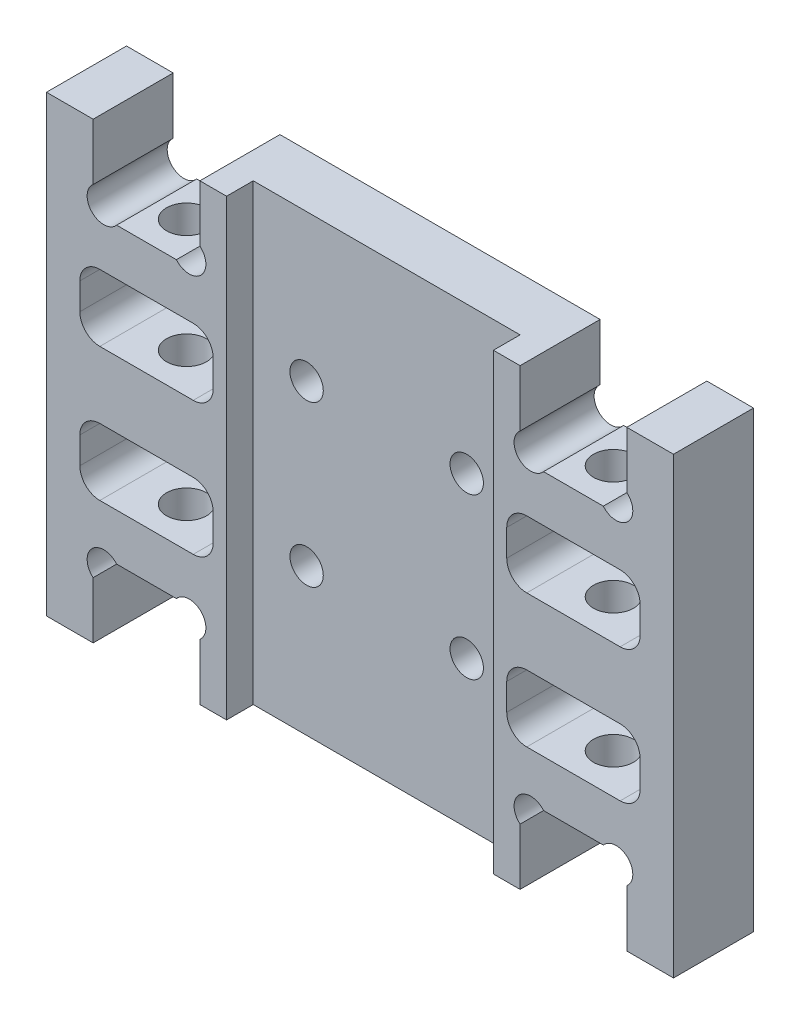
SolidWorks part; units mm, degrees
ref_plane "前视基准面" through (0, 0, 0) normal (0, 0, 1) x (1, 0, 0)
ref_plane "上视基准面" through (0, 0, 0) normal (0, 1, 0) x (1, 0, 0)
ref_plane "右视基准面" through (0, 0, 0) normal (1, 0, 0) x (0, 0, -1)
sketch "草图1" plane through (0, 0, 0) normal (0, 0, 1) x (1, 0, 0)
  line L0 (0, 86.7562) -> (0, -64.6665) construction
  line L1 (-73.9598, 0) -> (104.5329, 0) construction
  line L2 (-25, -17) -> (-25, 17)
  line L3 (-25, 17) -> (-22, 17)
  line L4 (-22, 17) -> (-22, 11)
  line L5 (-22, 11) -> (-12, 11)
  line L6 (-12, 11) -> (-12, 17)
  line L7 (-12, 17) -> (12, 17)
  line L8 (-12, -17) -> (12, -17)
  line L9 (-12, -11) -> (-12, -17)
  line L10 (-22, -11) -> (-12, -11)
  line L11 (-22, -17) -> (-22, -11)
  line L12 (-25, -17) -> (-22, -17)
  line L13 (25, -17) -> (22, -17)
  line L14 (22, -17) -> (22, -11)
  line L15 (22, -11) -> (12, -11)
  line L16 (12, -11) -> (12, -17)
  line L17 (12, 11) -> (12, 17)
  line L18 (22, 11) -> (12, 11)
  line L19 (22, 17) -> (22, 11)
  line L20 (25, 17) -> (22, 17)
  line L21 (25, -17) -> (25, 17)
  line L22 (-17, 11) -> (-17, -11) construction
  line L23 (-23, 11) -> (-23, -11) construction
  line L24 (-11, 11) -> (-11, -11) construction
  point P18 (-25, 0)
  point P23 (0, -17)
  point P24 (0, 17)
  point P28 (25, 0)
  dimension "D1" = 17
  dimension "D2" = 6
  dimension "D3" = 10
  dimension "D4" = 3
  dimension "D5" = 17
  dimension "D6" = 6
  dimension "D7" = 6
extrude "凸台-拉伸1" add sketch "草图1" along normal blind 6
sketch "草图2" plane through (0, 0, 6) normal (0, 0, 1) x (1, 0, 0)
  line L0 (-16, 14) -> (-16, -10) construction
  line L3 (-25, 0) -> (25, 0) construction
  line L4 (-25, 17) -> (-25, -17) construction
  line L5 (25, -17) -> (25, 17) construction
  line L6 (-21, -2.5) -> (-11, -7.5) construction
  line L7 (-21, 7.5) -> (-11, 7.5)
  line L8 (-21, 7.5) -> (-21, 2.5)
  line L9 (-21, 2.5) -> (-11, 2.5)
  line L10 (-11, 7.5) -> (-11, 2.5)
  line L11 (-21, 7.5) -> (-11, 2.5) construction
  line L12 (-21, 2.5) -> (-11, 7.5) construction
  line L13 (-21, -7.5) -> (-11, -2.5) construction
  line L14 (-11, -7.5) -> (-11, -2.5)
  line L15 (-21, -2.5) -> (-11, -2.5)
  line L16 (-21, -7.5) -> (-21, -2.5)
  line L17 (-21, -7.5) -> (-11, -7.5)
  line L18 (0, 17) -> (0, -17) construction
  line L19 (12, 17) -> (-12, 17) construction
  line L20 (-12, -17) -> (12, -17) construction
  line L21 (21, -7.5) -> (11, -2.5) construction
  line L22 (21, 2.5) -> (11, 7.5) construction
  line L23 (21, 7.5) -> (11, 2.5) construction
  line L24 (21, -2.5) -> (11, -7.5) construction
  line L25 (16, 14) -> (16, -10) construction
  line L26 (21, -7.5) -> (11, -7.5)
  line L27 (21, -7.5) -> (21, -2.5)
  line L28 (21, -2.5) -> (11, -2.5)
  line L29 (11, -7.5) -> (11, -2.5)
  line L30 (11, 7.5) -> (11, 2.5)
  line L31 (21, 2.5) -> (11, 2.5)
  line L32 (21, 7.5) -> (21, 2.5)
  line L33 (21, 7.5) -> (11, 7.5)
  line L34 (11, 2.5) -> (21, -2.5) construction
  line L35 (-11, -2.5) -> (-21, -2.5) construction
  line L36 (-11, -2.5) -> (-11, 2.5) construction
  line L37 (-11, 2.5) -> (-21, 2.5) construction
  line L38 (-21, -2.5) -> (-21, 2.5) construction
  line L39 (-11, -2.5) -> (-21, 2.5) construction
  line L40 (-11, 2.5) -> (-21, -2.5) construction
  line L41 (11, -2.5) -> (21, 2.5) construction
  line L42 (21, -2.5) -> (21, 2.5) construction
  line L43 (11, 2.5) -> (21, 2.5) construction
  line L44 (11, -2.5) -> (11, 2.5) construction
  line L45 (11, -2.5) -> (21, -2.5) construction
  point P2 (-16, 0)
  point P12 (-16, 5)
  point P17 (-16, 2)
  point P22 (-16, -5)
  point P39 (16, -5)
  point P40 (16, 5)
  point P46 (16, 0)
  dimension "D1" = 10
  dimension "D2" = 5
  dimension "D3" = 12
  dimension "D4" = 5
  dimension "D5" = 16
  dimension "D6" = 5
  dimension "D7" = 10
extrude "切除-拉伸1" cut sketch "草图2" against normal through all
sketch "草图3" plane through (0, -11, 0) normal (0, -1, 0) x (1, 0, 0)
  line L0 (-25, 3) -> (25, 3) construction
  line L1 (-25, 6) -> (-25, 0) construction
  line L2 (25, 6) -> (25, 0) construction
  line L3 (-16, 6) -> (-16, 0) construction
  line L5 (-22, 0) -> (-12, 0) construction
  line L6 (0, 0) -> (0, 6) construction
  line L7 (-12, 6) -> (12, 6) construction
  line L8 (-12, 6) -> (-12, 0) construction
  circle A0 centre (-16, 3) radius 1.5
  circle A1 centre (16, 3) radius 1.5
  dimension "D1" = 3
  dimension "D2" = 4
extrude "切除-拉伸2" cut sketch "草图3" against normal through all
sketch "草图4" plane through (0, 0, 6) normal (0, 0, 1) x (1, 0, 0)
  line L1 (-10, 17) -> (10, 17)
  line L2 (-10, 17) -> (-10, -17)
  line L3 (-10, -17) -> (10, -17)
  line L4 (10, 17) -> (10, -17)
  line L5 (-10, 17) -> (10, -17) construction
  line L6 (-10, -17) -> (10, 17) construction
  line L7 (-12, -17) -> (12, -17) construction
  point P0 (0, 0)
  dimension "D1" = 20
extrude "切除-拉伸3" cut sketch "草图4" against normal blind 2
sketch "草图5" plane through (0, 0, 4) normal (0, 0, 1) x (1, 0, 0)
  line L1 (-6, 6) -> (6, 6) construction
  line L2 (-6, 6) -> (-6, -6) construction
  line L3 (-6, -6) -> (6, -6) construction
  line L4 (6, 6) -> (6, -6) construction
  line L5 (-6, 6) -> (6, -6) construction
  line L6 (-6, -6) -> (6, 6) construction
  circle A0 centre (-6, 6) radius 1.25
  circle A1 centre (6, 6) radius 1.25
  circle A2 centre (-6, -6) radius 1.25
  circle A3 centre (6, -6) radius 1.25
  point P0 (0, 0)
  dimension "D3" = 2.5
  dimension "D1" = 12
  dimension "D2" = 12
extrude "切除-拉伸4" cut sketch "草图5" against normal through all
cosmetic thread "装饰螺纹线1" [suppressed] parameters "D2"=4
cosmetic thread "装饰螺纹线2" [suppressed] parameters "D2"=4
cosmetic thread "装饰螺纹线3" [suppressed] parameters "D2"=4
cosmetic thread "装饰螺纹线4" [suppressed] parameters "D2"=4
sketch "草图6" plane through (0, 0, 6) normal (0, 0, 1) x (1, 0, 0)
  line L0 (0, 22.7228) -> (0, -22.1506) construction
  line L1 (-12, 14) -> (12, 14) construction
  line L2 (-12, 17) -> (-12, 11) construction
  line L3 (12, 11) -> (12, 17) construction
  line L4 (-10, 17) -> (-10, -17) construction
  line L5 (-13, 15.5) -> (-1, 15.5) construction
  line L6 (-13, 15.5) -> (-13, 12.5) construction
  line L7 (-13, 12.5) -> (-1, 12.5) construction
  line L8 (-1, 15.5) -> (-1, 12.5) construction
  line L9 (-13, 15.5) -> (-1, 12.5) construction
  line L10 (-13, 12.5) -> (-1, 15.5) construction
  line L11 (-12, 11) -> (-22, 11) construction
  line L12 (-22, -11) -> (-12, -11) construction
  line L13 (0, 0) -> (25, 0) construction
  line L14 (25, -17) -> (25, 17) construction
  circle A0 centre (-7, 14) radius 1.5
  circle A1 centre (7, 14) radius 1.5
  circle A2 centre (7, -14) radius 1.5
  circle A3 centre (-7, -14) radius 1.5
  point P9 (-7, 14)
  point P14 (0, 14)
  dimension "D5" = 3
  dimension "D1" = 12
  dimension "D2" = 12
  dimension "D3" = 7
  dimension "D4" = 3
  dimension "D6" = 3
  dimension "D7" = 22
extrude "切除-拉伸6" [suppressed] cut sketch "草图6" against normal through all contours A0 | A1 | A3 | A2
cosmetic thread "装饰螺纹线5" [suppressed] parameters "D2"=4
cosmetic thread "装饰螺纹线6" [suppressed] parameters "D2"=4
cosmetic thread "装饰螺纹线7" [suppressed] parameters "D2"=4
cosmetic thread "装饰螺纹线8" [suppressed] parameters "D2"=4
sketch "草图7" plane through (0, 0, 6) normal (0, 0, 1) x (1, 0, 0)
  line L1 (-10, 17) -> (-12, 17) construction
  line L2 (-11.5, 17) -> (11.5, 17)
  line L3 (-11.5, 17) -> (-11.5, 11)
  line L4 (-11.5, 11) -> (11.5, 11)
  line L5 (11.5, 17) -> (11.5, 11)
  line L6 (22, 11) -> (12, 11) construction
  line L7 (-10, 17) -> (-10, -17) construction
  line L8 (10, -17) -> (10, 17) construction
  line L9 (-29.3966, 0) -> (33.4524, 0) construction
  line L10 (11.5, -17) -> (11.5, -11)
  line L11 (-11.5, -11) -> (11.5, -11)
  line L12 (-11.5, -17) -> (-11.5, -11)
  line L13 (-11.5, -17) -> (11.5, -17)
  dimension "D1" = 1.5
  dimension "D2" = 1.5
extrude "切除-拉伸8" [suppressed] cut sketch "草图7" against normal up to surface (2 mm away)
fillet "圆角1" [suppressed] radius 1.5
sketch "草图8" plane through (0, 0, 6) normal (0, 0, 1) x (1, 0, 0)
  circle A0 centre (-22, 11) radius 1
  circle A1 centre (-12, 11) radius 1
  circle A2 centre (12, 11) radius 1
  circle A3 centre (22, 11) radius 1
  circle A4 centre (-22, -11) radius 1
  circle A5 centre (-12, -11) radius 1
  circle A6 centre (12, -11) radius 1
  circle A7 centre (22, -11) radius 1
  dimension "D1" = 2
extrude "切除-拉伸9" [suppressed] cut sketch "草图8" against normal through all
fillet "圆角2" radius 1.5 16 edges at (21, -7.5, 3) (11, -7.5, 3) (21, 2.5, 3) (21, 7.5, 3) (11, 2.5, 3) (11, 7.5, 3) (-11, -7.5, 3) (-21, -7.5, 3) (-21, -2.5, 3) (-11, -2.5, 3) (-21, 2.5, 3) (-11, 2.5, 3) (-11, 7.5, 3) (-21, 7.5, 3) (11, -2.5, 3) (21, -2.5, 3)
sketch "草图9" plane through (0, 0, 6) normal (0, 0, 1) x (1, 0, 0)
  line L1 (-25, 17) -> (-23.5, 17)
  line L2 (-25, 17) -> (-25, -18)
  line L3 (-25, -18) -> (-23.5, -18)
  line L4 (-23.5, 17) -> (-23.5, -18)
  line L6 (25, 17) -> (23.5, 17)
  line L7 (25, 17) -> (25, -18)
  line L8 (25, -18) -> (23.5, -18)
  line L9 (23.5, 17) -> (23.5, -18)
  dimension "D1" = 1.5
extrude "切除-拉伸10" cut sketch "草图9" against normal through all
sketch "草图10" plane through (0, 0, 6) normal (0, 0, 1) x (1, 0, 0)
  line L0 (-12, 11) -> (-22, 11) construction
  line L1 (-22, 17) -> (-20, 17)
  line L2 (-22, 17) -> (-22, 11)
  line L3 (-22, 11) -> (-20, 11)
  line L4 (-20, 17) -> (-20, 11)
  line L5 (22, 11) -> (12, 11) construction
  line L6 (22, 17) -> (20, 17)
  line L7 (22, 17) -> (22, 11)
  line L8 (22, 11) -> (20, 11)
  line L9 (20, 17) -> (20, 11)
  line L10 (0, 0) -> (43.6529, 0) construction
  line L11 (20, -17) -> (20, -11)
  line L12 (22, -11) -> (20, -11)
  line L13 (22, -17) -> (22, -11)
  line L14 (22, -17) -> (20, -17)
  line L15 (-20, -17) -> (-20, -11)
  line L16 (-22, -11) -> (-20, -11)
  line L17 (-22, -17) -> (-22, -11)
  line L18 (-22, -17) -> (-20, -17)
  dimension "D1" = 2
  dimension "D2" = 2
extrude "凸台-拉伸2" add sketch "草图10" against normal up to surface (6 mm away) up to face at (7.25, 6, 0)
sketch "草图11" plane through (0, 0, 6) normal (0, 0, 1) x (1, 0, 0)
  line L0 (-12, 11) -> (-20, 11) construction
  line L1 (-20, 11) -> (-20, 17) construction
  line L2 (-16, 11) -> (-16, 18.3437) construction
  line L3 (0, 17) -> (0, -17) construction
  line L4 (10, 17) -> (-10, 17) construction
  line L5 (-10, -17) -> (10, -17) construction
  line L6 (0, 0) -> (23.5, 0) construction
  line L7 (23.5, 17) -> (23.5, -17) construction
  circle A0 centre (-19.2, 11.8) radius 1.25
  circle A1 centre (-12.8, 11.8) radius 1.25
  circle A2 centre (12.8, 11.8) radius 1.25
  circle A3 centre (19.2, 11.8) radius 1.25
  circle A4 centre (19.2, -11.8) radius 1.25
  circle A5 centre (12.8, -11.8) radius 1.25
  circle A6 centre (-12.8, -11.8) radius 1.25
  circle A7 centre (-19.2, -11.8) radius 1.25
  dimension "D1" = 2.5
  dimension "D2" = 0.8
  dimension "D3" = 0.8
extrude "切除-拉伸11" cut sketch "草图11" against normal through all
equation "\"D2@草图7\"=\"D1@草图7\""
